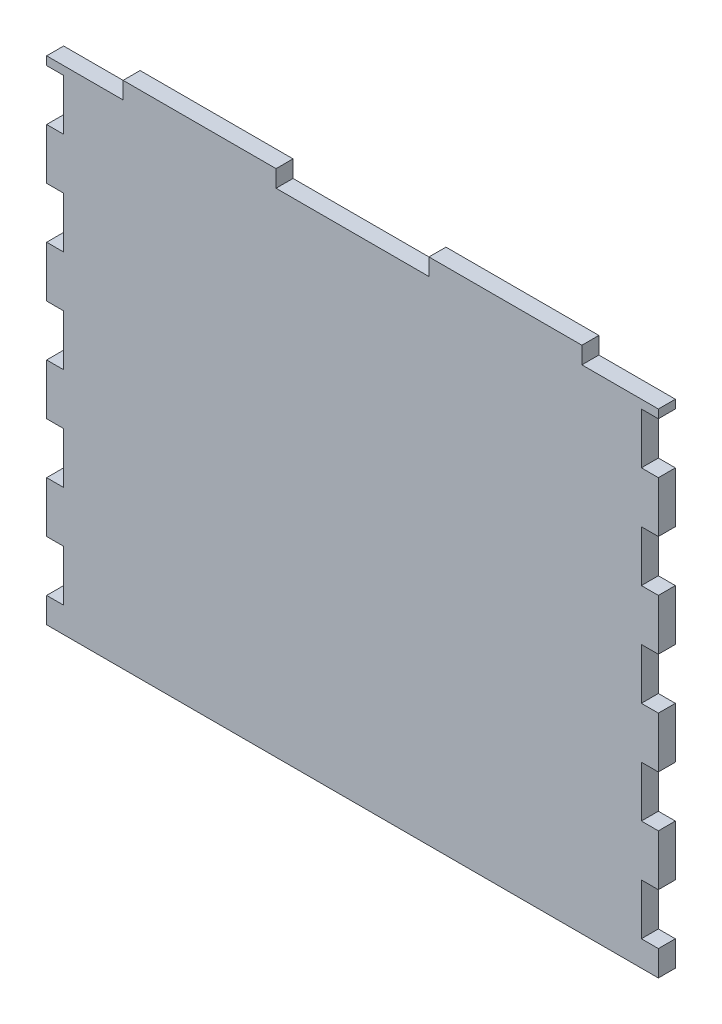
SolidWorks part; units mm, degrees
ref_plane "Front Plane" through (0, 0, 0) normal (0, 0, 1) x (1, 0, 0)
ref_plane "Top Plane" through (0, 0, 0) normal (0, 1, 0) x (1, 0, 0)
ref_plane "Right Plane" through (0, 0, 0) normal (1, 0, 0) x (0, 0, -1)
sketch "Sketch1" plane through (0, 0, 0) normal (0, 0, 1) x (1, 0, 0)
  line L0 (85.725, 100.551) -> (114.3, 100.551) construction
  line L1 (85.725, 95.25) -> (28.575, 95.25)
  line L2 (114.3, 88.9) -> (114.3, 85.725)
  line L3 (114.3, -95.25) -> (-114.3, -95.25)
  line L4 (-114.3, 88.9) -> (-114.3, 85.725)
  line L5 (114.3, 95.25) -> (-114.3, -95.25) construction
  line L6 (114.3, -95.25) -> (-114.3, 95.25) construction
  line L7 (85.725, 95.25) -> (85.725, 88.9)
  line L8 (28.575, 95.25) -> (28.575, 88.9)
  line L9 (-28.575, 95.25) -> (-28.575, 88.9)
  line L10 (-85.725, 95.25) -> (-85.725, 88.9)
  line L11 (-85.725, 88.9) -> (-114.3, 88.9)
  line L12 (-28.575, 88.9) -> (28.575, 88.9)
  line L13 (85.725, 88.9) -> (114.3, 88.9)
  line L14 (-28.575, 95.25) -> (-85.725, 95.25)
  line L15 (124.9833, 95.25) -> (124.9833, 85.725) construction
  line L16 (114.3, 85.725) -> (107.95, 85.725)
  line L17 (114.3, 66.675) -> (107.95, 66.675)
  line L18 (114.3, 47.625) -> (107.95, 47.625)
  line L19 (114.3, 28.575) -> (107.95, 28.575)
  line L20 (114.3, 9.525) -> (107.95, 9.525)
  line L21 (114.3, -9.525) -> (107.95, -9.525)
  line L22 (114.3, -28.575) -> (107.95, -28.575)
  line L23 (114.3, -47.625) -> (107.95, -47.625)
  line L24 (114.3, -66.675) -> (107.95, -66.675)
  line L25 (114.3, -85.725) -> (107.95, -85.725)
  line L26 (107.95, -9.525) -> (107.95, 9.525)
  line L27 (107.95, -85.725) -> (107.95, -66.675)
  line L28 (0, 49.4398) -> (0, -43.8374) construction
  line L29 (-114.3, -85.725) -> (-107.95, -85.725)
  line L30 (-114.3, -66.675) -> (-107.95, -66.675)
  line L31 (-114.3, -47.625) -> (-107.95, -47.625)
  line L32 (-114.3, -28.575) -> (-107.95, -28.575)
  line L33 (-114.3, -9.525) -> (-107.95, -9.525)
  line L34 (-114.3, 9.525) -> (-107.95, 9.525)
  line L35 (-114.3, 28.575) -> (-107.95, 28.575)
  line L36 (-114.3, 47.625) -> (-107.95, 47.625)
  line L37 (-114.3, 66.675) -> (-107.95, 66.675)
  line L38 (-114.3, 85.725) -> (-107.95, 85.725)
  line L39 (-107.95, -47.625) -> (-107.95, -28.575)
  line L40 (-114.3, 66.675) -> (-114.3, 47.625)
  line L41 (-114.3, 28.575) -> (-114.3, 9.525)
  line L42 (-114.3, -9.525) -> (-114.3, -28.575)
  line L43 (-114.3, -47.625) -> (-114.3, -66.675)
  line L44 (-114.3, -85.725) -> (-114.3, -95.25)
  line L45 (-107.95, -85.725) -> (-107.95, -66.675)
  line L46 (-107.95, -9.525) -> (-107.95, 9.525)
  line L47 (-107.95, 28.575) -> (-107.95, 47.625)
  line L48 (-107.95, 66.675) -> (-107.95, 85.725)
  line L49 (114.3, 66.675) -> (114.3, 47.625)
  line L50 (114.3, 28.575) -> (114.3, 9.525)
  line L51 (107.95, 66.675) -> (107.95, 85.725)
  line L52 (107.95, 28.575) -> (107.95, 47.625)
  line L53 (114.3, -9.525) -> (114.3, -28.575)
  line L54 (114.3, -47.625) -> (114.3, -66.675)
  line L55 (107.95, -47.625) -> (107.95, -28.575)
  line L56 (114.3, -85.725) -> (114.3, -95.25)
  point P0 (0, 0)
  dimension "D1" = 190.5
  dimension "D2" = 228.6
  dimension "D3" = 28.575
  dimension "D4" = 6.35
  dimension "D5" = 4
  dimension "D6" = 9.525
  dimension "D7" = 6.35
  dimension "D9" = 3.175
  dimension "D8" = 10
extrude "Boss-Extrude1" add sketch "Sketch1" along normal blind 6.35
sketch "Sketch2" plane through (0, 0, 6.35) normal (0, 0, 1) x (1, 0, 0)
  line L0 (-114.3, 88.9) -> (114.3, 88.9)
  line L1 (-107.95, -66.675) -> (-104.775, -66.675)
  line L2 (-104.775, -66.675) -> (-104.775, -95.25)
  line L3 (-114.3, -95.25) -> (114.3, -95.25) construction
  line L4 (107.95, -66.675) -> (104.775, -66.675)
  line L5 (104.775, -66.675) -> (104.775, -95.25)
  dimension "D1" = 3.175
  dimension "D2" = 3.175
